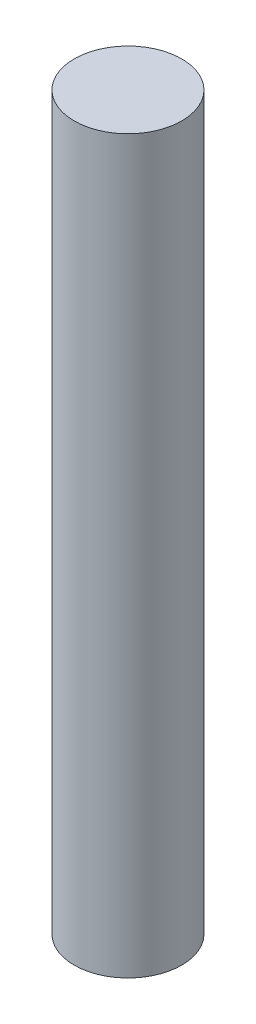
SolidWorks part; units mm, degrees
ref_plane "Alzado" through (0, 0, 0) normal (0, 0, 1) x (1, 0, 0)
ref_plane "Planta" through (0, 0, 0) normal (0, 1, 0) x (1, 0, 0)
ref_plane "Vista lateral" through (0, 0, 0) normal (1, 0, 0) x (0, 0, -1)
sketch "Croquis1" plane through (0, 0, 0) normal (0, 1, 0) x (1, 0, 0)
  circle A0 centre (0, 0) radius 2.5
  dimension "D1" = 5
extrude "Saliente-Extruir1" add sketch "Croquis1" along normal blind 34
